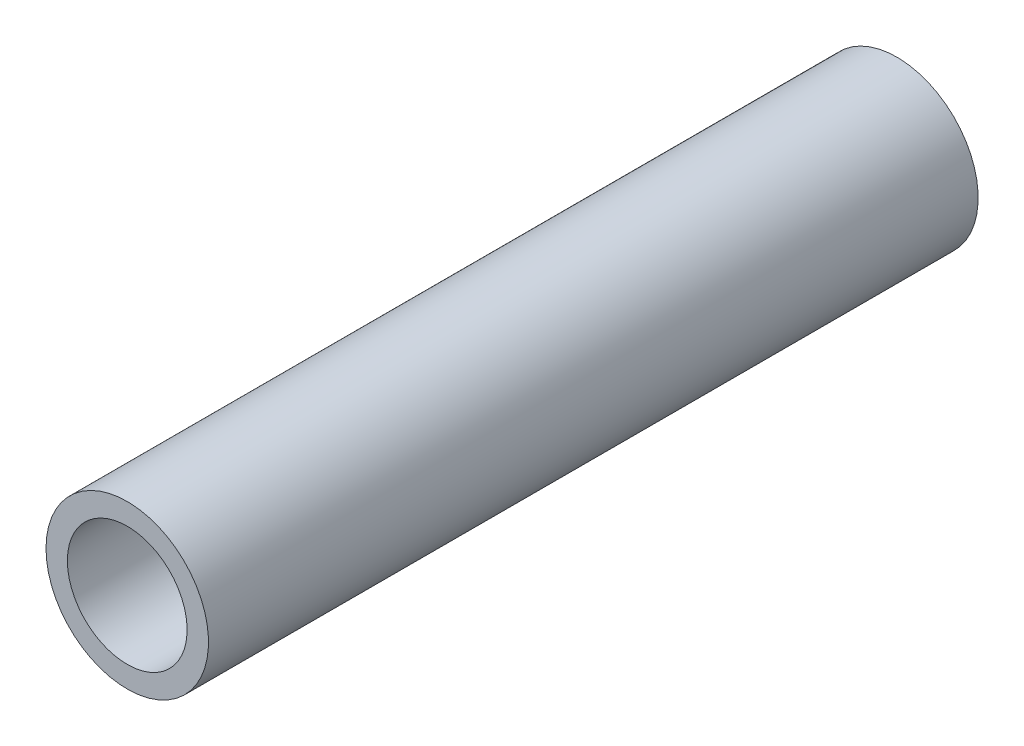
SolidWorks part; units mm, degrees
ref_plane "Front Plane" through (0, 0, 0) normal (0, 0, 1) x (1, 0, 0)
ref_plane "Top Plane" through (0, 0, 0) normal (0, 1, 0) x (1, 0, 0)
ref_plane "Right Plane" through (0, 0, 0) normal (1, 0, 0) x (0, 0, -1)
sketch "Sketch2" plane through (0, 0, 0) normal (0, 0, 1) x (1, 0, 0)
  circle A0 centre (0, 0) radius 7
  circle A1 centre (0, 0) radius 9.5
  dimension "D1" = 2.5
extrude "Boss-Extrude2" add sketch "Sketch2" along normal blind 90
